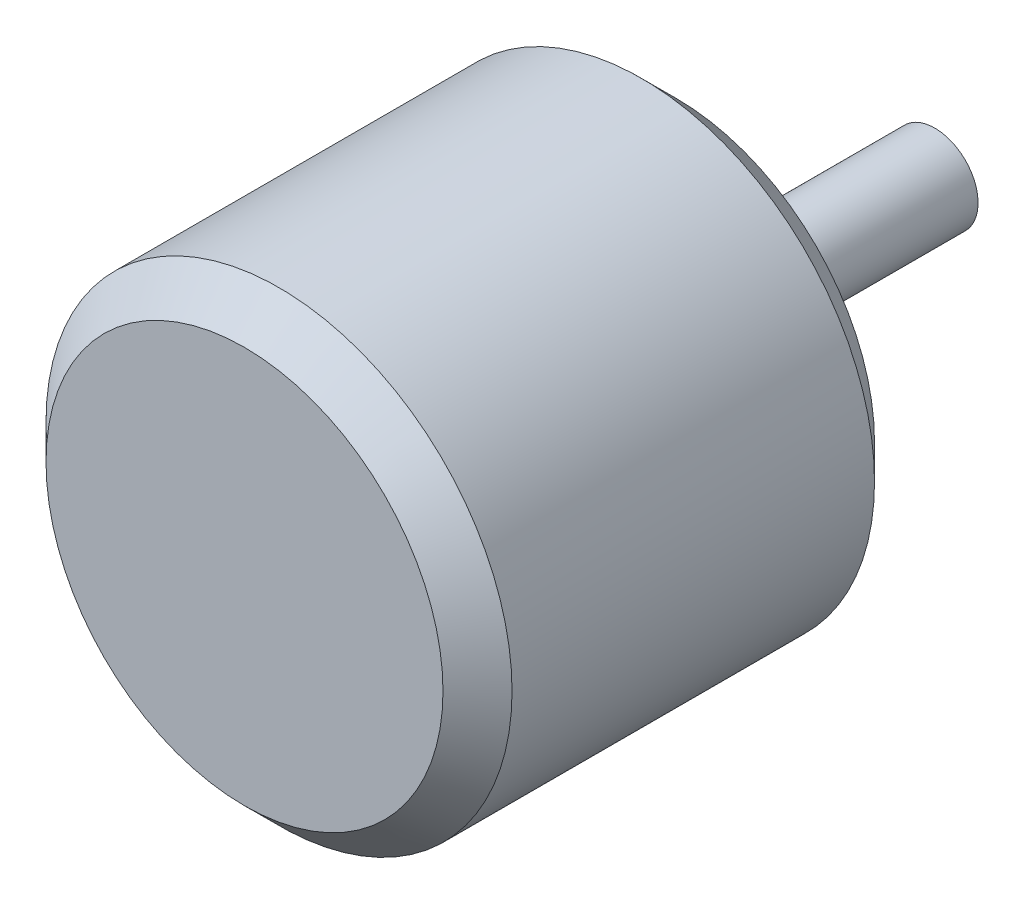
SolidWorks part; units mm, degrees
ref_plane "정면" through (0, 0, 0) normal (0, 0, 1) x (1, 0, 0)
ref_plane "윗면" through (0, 0, 0) normal (0, 1, 0) x (1, 0, 0)
ref_plane "우측면" through (0, 0, 0) normal (1, 0, 0) x (0, 0, -1)
sketch "스케치1" plane through (0, 0, 0) normal (0, 0, 1) x (1, 0, 0)
  circle A0 centre (0, 0) radius 13.5
  dimension "D1" = 27
extrude "보스-돌출1" add sketch "스케치1" along normal blind 25
chamfer "모따기1" distance 2 angle 45 2 edges at (13.5, 0, 25) (13.5, 0, 0)
sketch "스케치2" plane through (0, 0, 0) normal (0, 0, -1) x (-1, 0, 0)
  circle A0 centre (0, 0) radius 2.5
  dimension "D1" = 5
extrude "보스-돌출2" add sketch "스케치2" along normal blind 15
